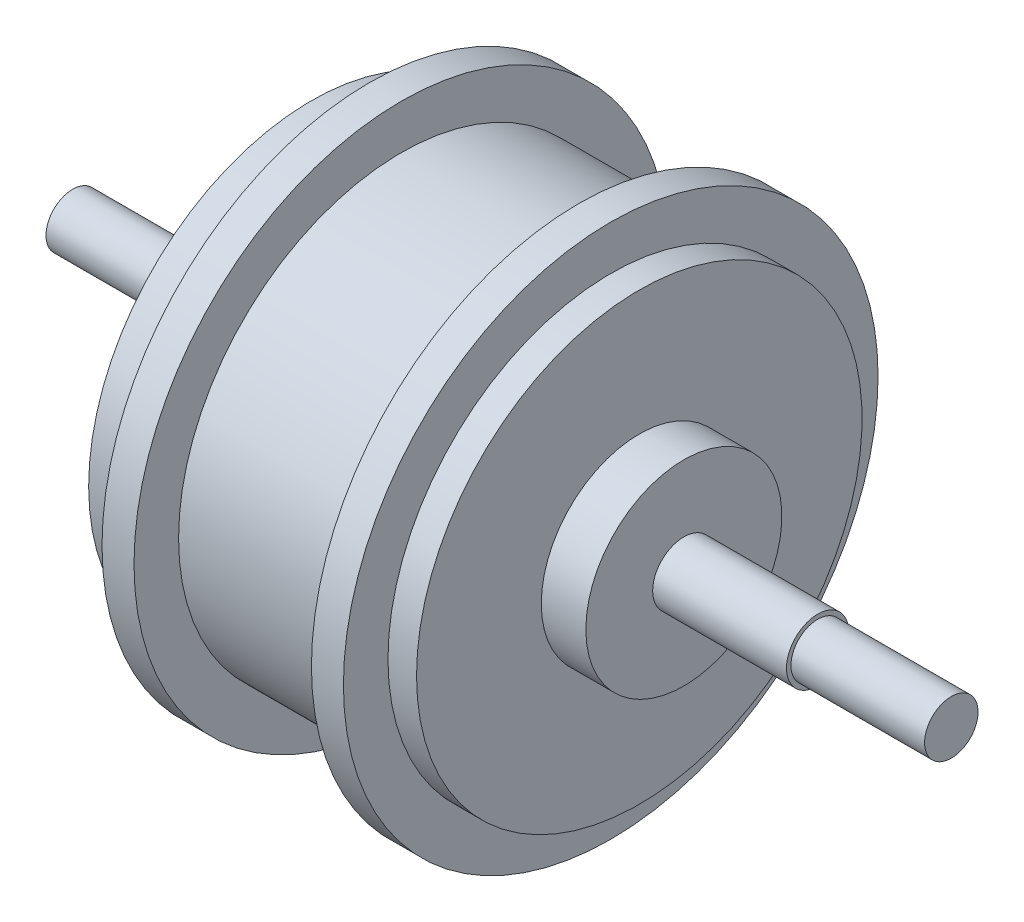
SolidWorks part; units mm, degrees
ref_plane "Front Plane" through (0, 0, 0) normal (0, 0, 1) x (1, 0, 0)
ref_plane "Top Plane" through (0, 0, 0) normal (0, 1, 0) x (1, 0, 0)
ref_plane "Right Plane" through (0, 0, 0) normal (1, 0, 0) x (0, 0, -1)
sketch "Sketch1" plane through (0, 0, 0) normal (0, 0, 1) x (1, 0, 0)
  line L0 (0, 0) -> (219.0485, 0) construction
  line L1 (0, 0) -> (0, 6)
  line L2 (0, 6) -> (33, 6)
  line L3 (33, 6) -> (33, 8.5)
  line L4 (33, 8.5) -> (43.5, 8.5)
  line L5 (66.569, 50) -> (66.569, 60)
  line L6 (73.751, 60) -> (66.569, 60)
  line L7 (73.751, 60) -> (73.751, 50)
  line L8 (66.569, 50) -> (53.569, 50)
  line L9 (53.569, 50) -> (49.8148, 36.3186)
  line L10 (43.5, 8.5) -> (43.5, 17)
  line L11 (43.5, 17) -> (49.8148, 17)
  line L12 (49.8148, 17) -> (49.8148, 36.3186)
  line L13 (73.751, 50) -> (113.569, 50)
  line L14 (113.569, 50) -> (113.569, 60)
  line L15 (113.569, 60) -> (120.751, 60)
  line L16 (120.751, 60) -> (120.751, 50)
  line L17 (120.751, 50) -> (127.16, 50)
  line L18 (127.16, 50) -> (127.16, 22)
  line L19 (127.16, 22) -> (137.16, 22)
  line L20 (137.16, 22) -> (137.16, 7)
  line L21 (137.16, 7) -> (167.1916, 7)
  line L22 (167.1916, 7) -> (167.1916, 6)
  line L23 (167.1916, 6) -> (197.1916, 6)
  line L24 (197.1916, 6) -> (197.1916, 0)
  line L25 (197.1916, 0) -> (0, 0)
  point P13 (70.16, 60)
  point P23 (117.16, 60)
  dimension "D1" = 33
  dimension "D2" = 8.5
  dimension "D3" = 10.5
  dimension "D4" = 26.66
  dimension "D5" = 60
  dimension "D6" = 10
  dimension "D7" = 13
  dimension "D8" = 17
  dimension "D9" = 47
  dimension "D10" = 10
  dimension "D11" = 22
  dimension "D12" = 10
  dimension "D13" = 6
  dimension "D14" = 134.2
  dimension "D15" = 30
  dimension "D16" = 7
revolve "Revolve1" add sketch "Sketch1" angle 360 about L0
